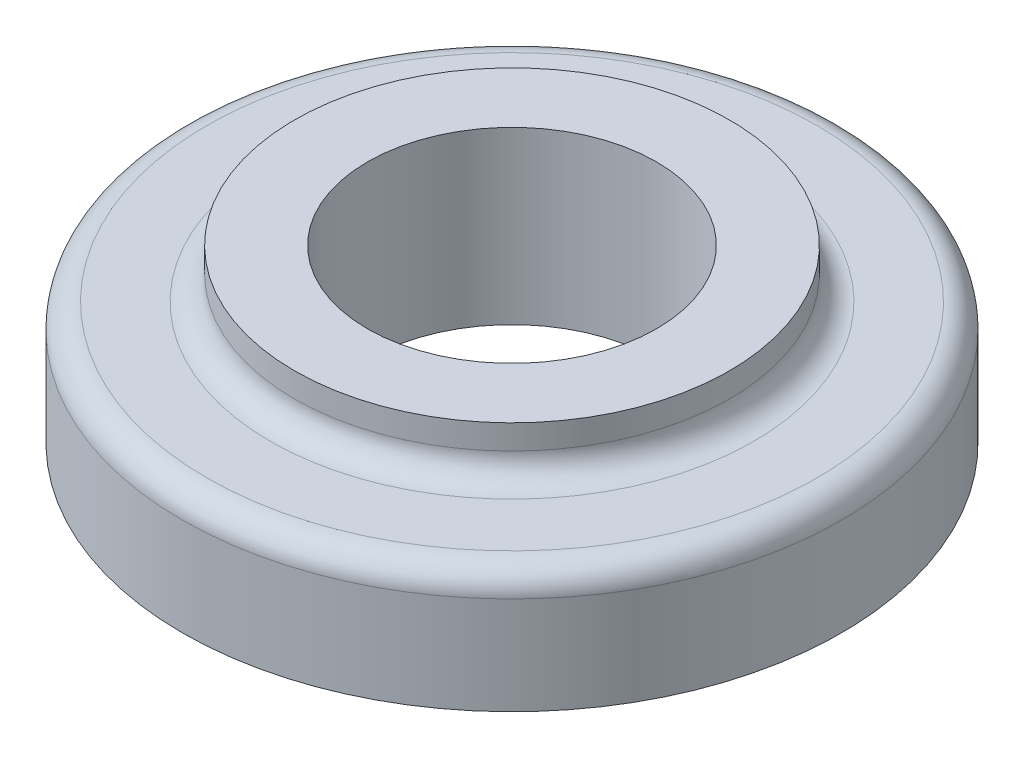
SolidWorks part; units mm, degrees
other "holefillets1"
ref_plane "Front Plane" through (0, 0, 0) normal (0, 0, 1) x (1, 0, 0)
ref_plane "Top Plane" through (0, 0, 0) normal (0, 1, 0) x (1, 0, 0)
ref_plane "Right Plane" through (0, 0, 0) normal (1, 0, 0) x (0, 0, -1)
sketch "Sketch1" plane through (0, 0, 0) normal (0, 1, 0) x (1, 0, 0)
  circle A0 centre (0, 0) radius 27.001
extrude "Boss-Extrude1" add sketch "Sketch1" along normal blind 10
sketch "Sketch2" plane through (0, 10, 0) normal (0, 1, 0) x (1, 0, 0)
  circle A1 centre (0, 0) radius 17.8113
extrude "Boss-Extrude3" add sketch "Sketch2" along normal blind 4 contours A1
sketch "Sketch3" plane through (0, 14, 0) normal (0, 1, 0) x (1, 0, 0)
  circle A0 centre (0, 0) radius 11.8444
extrude "Cut-Extrude2" cut sketch "Sketch3" against normal through all contours A0
fillet "Fillet1" radius 2 2 edges at (0, 10, 27.001) (0, 10, 17.8113)
